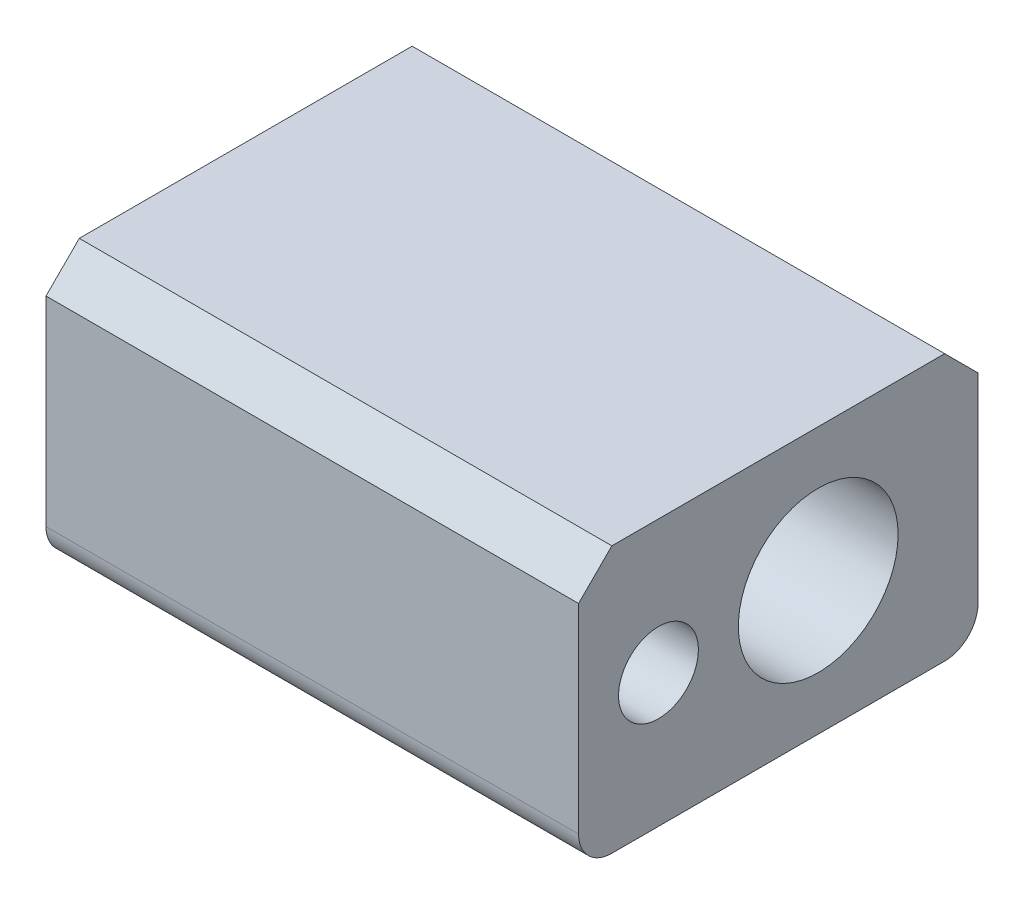
SolidWorks part; units mm, degrees
ref_plane "Front Plane" through (0, 0, 0) normal (1, 0, 0) x (0, 1, 0)
ref_plane "Top Plane" through (0, 0, 0) normal (0, 0, 1) x (0, 1, 0)
ref_plane "Right Plane" through (0, 0, 0) normal (0, 1, 0) x (-1, 0, 0)
sketch "Sketch1" plane through (0, 0, 0) normal (1, 0, 0) x (0, 1, 0)
  line L0 (0, -41.91) -> (0, 41.91) construction
  line L1 (25.4, -38.1) -> (-25.4, -38.1)
  line L2 (25.4, -38.1) -> (25.4, 38.1)
  line L3 (25.4, 38.1) -> (-25.4, 38.1)
  line L4 (-25.4, -38.1) -> (-25.4, 38.1)
  line L5 (25.4, -38.1) -> (-25.4, 38.1) construction
  line L6 (25.4, 38.1) -> (-25.4, -38.1) construction
  circle A0 centre (0, -7.62) radius 15.24
  circle A1 centre (0, 22.86) radius 7.62
  point P0 (0, 0)
  dimension "D3" = 30.48
  dimension "D5" = 15.24
  dimension "D1" = 50.8
  dimension "D2" = 76.2
  dimension "D4" = 30.48
  dimension "D6" = 15.24
extrude "Boss-Extrude1" add sketch "Sketch1" along normal blind 101.6
fillet "Fillet1" radius 6.35 2 edges at (50.8, -25.4, -38.1) (50.8, -25.4, 38.1)
chamfer "Chamfer1" distance 6.35 angle 45 2 edges at (50.8, 25.4, -38.1) (50.8, 25.4, 38.1)
